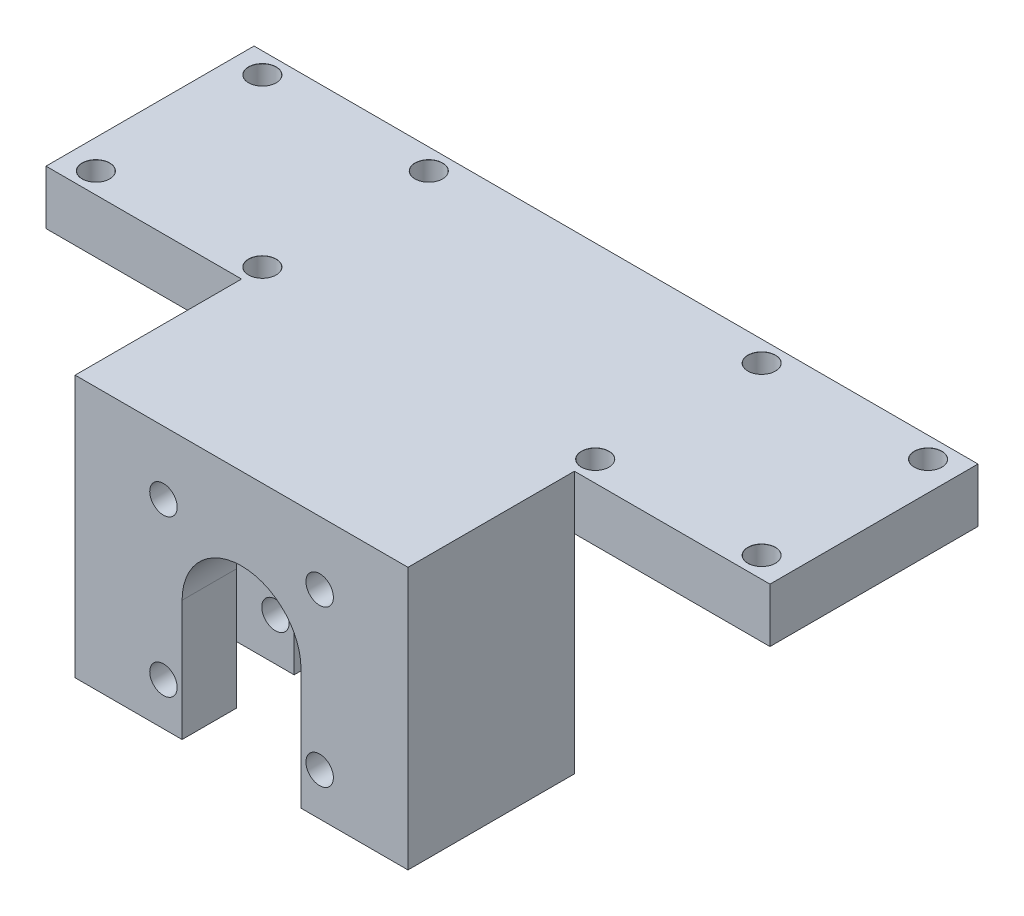
SolidWorks part; units mm, degrees
ref_plane "Front Plane" through (0, 0, 0) normal (0, 0, 1) x (1, 0, 0)
ref_plane "Top Plane" through (0, 0, 0) normal (0, 1, 0) x (1, 0, 0)
ref_plane "Right Plane" through (0, 0, 0) normal (1, 0, 0) x (0, 0, -1)
sketch "Sketch1" plane through (0, 0, 0) normal (0, 1, 0) x (1, 0, 0)
  line L1 (-87, 25) -> (87, 25)
  line L2 (-87, 25) -> (-87, -25)
  line L3 (-87, -25) -> (87, -25)
  line L4 (87, 25) -> (87, -25)
  line L5 (-87, 25) -> (87, -25) construction
  line L6 (-87, -25) -> (87, 25) construction
  point P0 (0, 0)
  dimension "D1" = 174
  dimension "D2" = 50
extrude "Boss-Extrude1" add sketch "Sketch1" along normal blind 13
hole_wizard "M6 Clearance Hole1" positions "Sketch4" profile "Sketch5" hole size "M6" standard "ANSI Metric" end condition up to next
sketch "Sketch4" plane through (0, 13, 0) normal (0, 1, 0) x (1, 0, 0)
  line L0 (-80, 20) -> (-40, 20) construction
  line L1 (-40, 20) -> (40, 20) construction
  line L2 (40, 20) -> (80, 20) construction
  line L4 (-80, 20) -> (-80, -20) construction
  line L6 (80, 20) -> (80, -20) construction
  point P0 (-80, 20)
  point P2 (-40, 20)
  point P4 (-80, -20)
  point P6 (-40, -20)
  point P8 (40, 20)
  point P10 (80, 20)
  point P12 (40, -20)
  point P14 (80, -20)
  point P39 (-80, 0)
  point P41 (0, 20)
  dimension "D1" = 40
  dimension "D2" = 40
  dimension "D3" = 80
sketch "Sketch5" plane through (-80, 13, -20) normal (1, 0, 0) x (0, 0, 1)
  line L0 (0, 0) -> (0, 13)
  line L1 (0, 13) -> (3.3, 13)
  line L2 (3.3, 13) -> (3.3, 0.021)
  line L3 (3.3, 0.021) -> (3.325, 0)
  line L5 (3.325, 0) -> (0, 0)
  line L6 (-3.3, 0.021) -> (-3.325, 0) construction
  line L11 (0, -6.35) -> (0, 107.95) construction
  dimension "Thru Hole Dia." = 6.6
  dimension "Thru Hole Depth" = 13
  dimension "Near C'Sink Dia." = 6.65
  dimension "Near C'Sink Angle" = 100
sketch "Sketch6" plane through (0, 0, 25) normal (0, 0, 1) x (1, 0, 0)
  line L0 (-87, 13) -> (87, 13) construction
  line L1 (-40, 13) -> (40, 13)
  line L2 (-40, 13) -> (-40, 0)
  line L3 (-40, 0) -> (40, 0)
  line L4 (40, 13) -> (40, 0)
  line L5 (-87, 0) -> (87, 0) construction
  dimension "D1" = 80
extrude "Boss-Extrude2" add sketch "Sketch6" along normal blind 40
sketch "Sketch7" plane through (0, 0, 0) normal (0, -1, 0) x (1, 0, 0)
  line L0 (40, 65) -> (40, 25) construction
  line L5 (40, 25) -> (87, 25) construction
  line L6 (-40, 65) -> (40, 65)
  line L7 (-40, 65) -> (-40, 25)
  line L8 (-40, 25) -> (40, 25)
  line L9 (40, 65) -> (40, 25)
extrude "Boss-Extrude3" add sketch "Sketch7" along normal blind 50
sketch "Sketch9" plane through (0, 0, 0) normal (0, 0, 1) x (1, 0, 0)
  circle A0 centre (0, -21) radius 14.29
  point P0 (0, -21)
  dimension "D2" = 28.58
  dimension "D1" = 21
extrude "Cut-Extrude2" cut sketch "Sketch9" against normal through all and the other way through all
hole_wizard "M6 Clearance Hole2" positions "Sketch12" profile "Sketch13" hole size "M6" standard "ANSI Metric"
sketch "Sketch12" plane through (0, 0, 25) normal (0, 0, 1) x (1, 0, 0)
  line L0 (-18.7701, -2.2299) -> (0, -21) construction
  line L1 (0, -21) -> (-18.7701, -39.7701) construction
  line L3 (0, -21) -> (18.7701, -39.7701) construction
  line L5 (0, -21) -> (18.7701, -2.2299) construction
  line L6 (-18.7701, -2.2299) -> (-18.7701, -39.7701) construction
  line L7 (-18.7701, -39.7701) -> (18.7701, -39.7701) construction
  point P0 (-18.7701, -2.2299)
  point P2 (-18.7701, -39.7701)
  point P4 (18.7701, -2.2299)
  point P6 (18.7701, -39.7701)
  dimension "D1" = 53.09
sketch "Sketch13" plane through (-18.7701, -2.2299, 25) normal (1, 0, 0) x (0, 1, 0)
  line L0 (0, 0) -> (0, 40)
  line L1 (0, 40) -> (3.3, 40)
  line L2 (3.3, 40) -> (3.3, 0.021)
  line L3 (3.3, 0.021) -> (3.325, 0)
  line L5 (3.325, 0) -> (0, 0)
  line L6 (-3.3, 0.021) -> (-3.325, 0) construction
  line L11 (0, -6.35) -> (0, 107.95) construction
  dimension "Thru Hole Dia." = 6.6
  dimension "Thru Hole Depth" = 40
  dimension "Near C'Sink Dia." = 6.65
  dimension "Near C'Sink Angle" = 100
ref_plane "Plane1" through (0, 0, 45) normal (0, 0, 1) x (1, 0, 0)
sketch "Sketch16" plane through (0, 0, 45) normal (0, 0, 1) x (1, 0, 0)
  line L0 (-33.22, -21) -> (-33.22, -50)
  line L1 (40, -50) -> (-40, -50) construction
  line L2 (-33.22, -50) -> (33.22, -50)
  line L3 (33.22, -50) -> (33.22, -21)
  arc A1 (-33.22, -21) -> (33.22, -21) centre (0, -21) cw
  circle A2 centre (0, -21) radius 14.29 construction
  dimension "D1" = 33.22
extrude "Cut-Extrude3" cut sketch "Sketch16" against normal blind 6.93 and the other way blind 6.93
sketch "Sketch17" plane through (0, 0, 65) normal (0, 0, 1) x (1, 0, 0)
  line L0 (-14.29, -21) -> (-14.29, -50)
  line L1 (40, -50) -> (-40, -50) construction
  line L2 (-14.29, -50) -> (14.29, -50)
  line L3 (14.29, -50) -> (14.29, -21)
  line L4 (14.29, -21) -> (-14.29, -21)
  circle A0 centre (0, -21) radius 14.29 construction
extrude "Cut-Extrude4" cut sketch "Sketch17" against normal through all
sketch "Sketch19" plane through (0, 0, -25) normal (0, 0, -1) x (-1, 0, 0)
  line L0 (-30.6183, 0) -> (-24.1183, 6.5)
  line L1 (-21.2366, 0) -> (-40, 0) construction
  line L2 (-24.1183, 6.5) -> (24.1183, 6.5)
  line L3 (24.1183, 6.5) -> (30.6183, 0)
  line L4 (40, 0) -> (21.2366, 0) construction
  line L5 (30.6183, 0) -> (-30.6183, 0)
  line L6 (-87, 13) -> (-87, 0) construction
  point P4 (0, 6.5)
  point P13 (-87, 6.5)
  dimension "D1" = 45
extrude "Cut-Extrude5" cut sketch "Sketch19" against normal up to surface (50 mm away) up to face at (-22.0951, -39.7701, 25)
